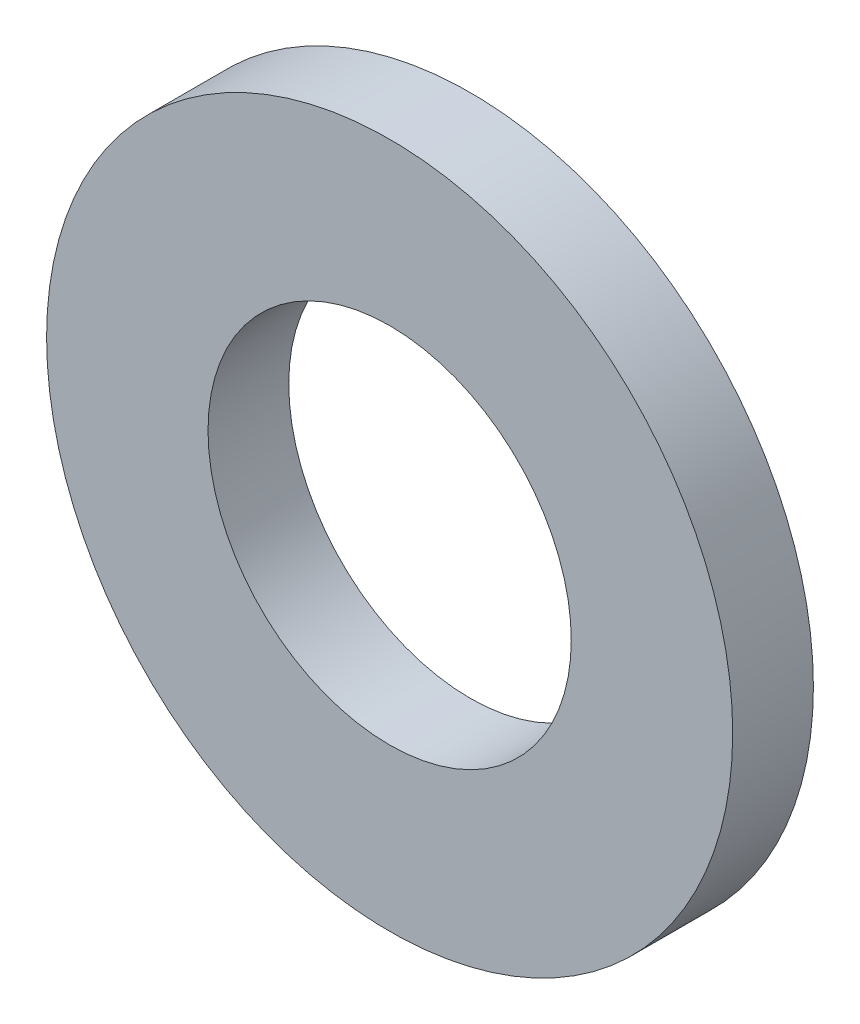
SolidWorks part; units mm, degrees
material "Rubber"
ref_plane "Front Plane" through (0, 0, 0) normal (0, 0, 1) x (1, 0, 0)
ref_plane "Top Plane" through (0, 0, 0) normal (0, 1, 0) x (1, 0, 0)
ref_plane "Right Plane" through (0, 0, 0) normal (1, 0, 0) x (0, 0, -1)
sketch "Sketch1" plane through (0, 0, 0) normal (0, 0, 1) x (1, 0, 0)
  circle A0 centre (0, 0) radius 22.5
  circle A1 centre (0, 0) radius 42.5
  dimension "D1" = 45
  dimension "D2" = 85
extrude "Boss-Extrude1" add sketch "Sketch1" along normal blind 10
